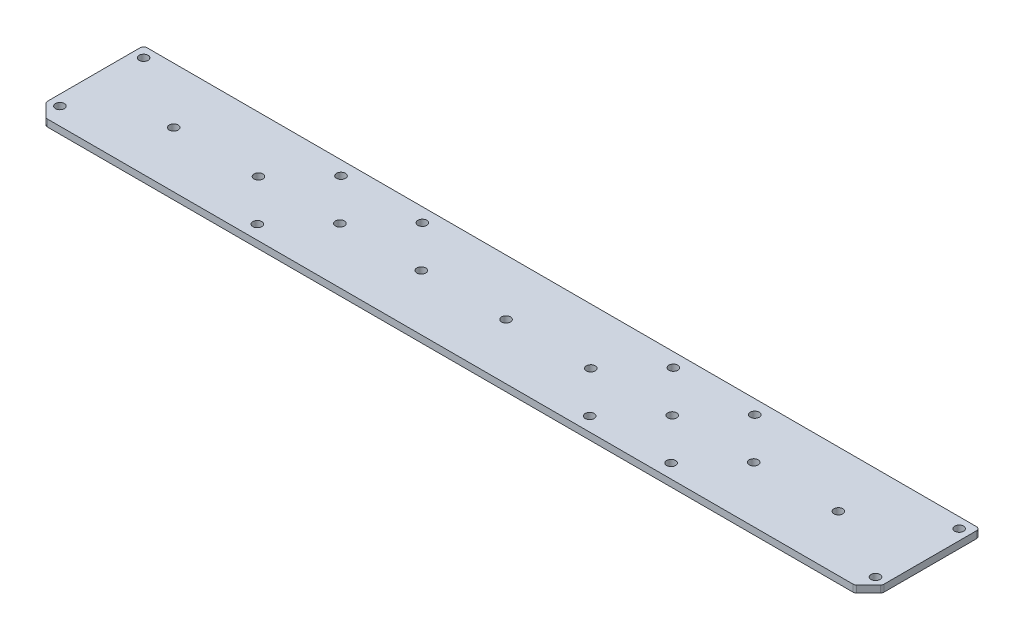
SolidWorks part; units mm, degrees
ref_plane "Front Plane" through (0, 0, 0) normal (0, 0, 1) x (1, 0, 0)
ref_plane "Top Plane" through (0, 0, 0) normal (0, 1, 0) x (1, 0, 0)
ref_plane "Right Plane" through (0, 0, 0) normal (1, 0, 0) x (0, 0, -1)
sketch "Sketch2" plane through (0, 0, 0) normal (0, 1, 0) x (1, 0, 0)
  line L0 (0, 7.0076) -> (0, 50.8)
  line L1 (0, 50.8) -> (381, 50.8)
  line L2 (381, 50.8) -> (381, 7.0076)
  line L3 (373.9924, 0) -> (7.0076, 0)
  line L4 (5.885, 0.465) -> (0.465, 5.885) construction
  line L5 (5.885, 0.465) -> (0.465, 5.885)
  line L6 (375.115, 0.465) -> (380.535, 5.885) construction
  line L7 (375.115, 0.465) -> (380.535, 5.885)
  line L8 (336.5758, 50.8) -> (379.4125, 50.8) construction
  arc A0 (5.885, 0.465) -> (7.0076, 0) centre (7.0076, 1.5875) ccw construction
  arc A1 (0, 7.0076) -> (0.465, 5.885) centre (1.5875, 7.0076) ccw construction
  arc A2 (5.885, 0.465) -> (7.0076, 0) centre (7.0076, 1.5875) ccw
  arc A3 (0, 7.0076) -> (0.465, 5.885) centre (1.5875, 7.0076) ccw
  arc A4 (373.9924, 0) -> (375.115, 0.465) centre (373.9924, 1.5875) ccw construction
  arc A6 (373.9924, 0) -> (375.115, 0.465) centre (373.9924, 1.5875) ccw
  arc A8 (380.535, 5.885) -> (381, 7.0076) centre (379.4125, 7.0076) ccw construction
  arc A9 (380.535, 5.885) -> (381, 7.0076) centre (379.4125, 7.0076) ccw
extrude "Boss-Extrude1" add sketch "Sketch2" along normal blind 3.175
sketch "Sketch3" plane through (0, 0, 0) normal (0, 1, 0) x (1, 0, 0)
  circle A25 centre (4.7625, 7.9375) radius 2.032 construction
  circle A31 centre (4.7625, 46.0375) radius 2.032 construction
  circle A63 centre (376.2375, 7.9375) radius 2.032 construction
  circle A64 centre (376.2375, 46.0375) radius 2.032 construction
  circle A67 centre (4.7625, 7.9375) radius 2.032
  circle A68 centre (4.7625, 46.0375) radius 2.032
  circle A72 centre (376.2375, 7.9375) radius 2.032
  circle A73 centre (376.2375, 46.0375) radius 2.032
  circle A123 centre (341.884, 25.4) radius 2.032 construction
  circle A124 centre (247.65, 44.45) radius 2.032 construction
  circle A125 centre (284.734, 44.45) radius 2.032 construction
  circle A128 centre (247.65, 6.35) radius 2.032 construction
  circle A129 centre (284.734, 6.35) radius 2.032 construction
  circle A132 centre (190.5, 25.4) radius 2.032 construction
  circle A135 centre (133.35, 44.45) radius 2.032 construction
  circle A136 centre (96.266, 44.45) radius 2.032 construction
  circle A137 centre (96.266, 6.35) radius 2.032 construction
  circle A140 centre (77.724, 25.4) radius 2.032 construction
  circle A141 centre (39.116, 25.4) radius 2.032 construction
  circle A142 centre (341.884, 25.4) radius 2.032
  circle A143 centre (247.65, 44.45) radius 2.032
  circle A144 centre (284.734, 44.45) radius 2.032
  circle A147 centre (247.65, 6.35) radius 2.032
  circle A148 centre (284.734, 6.35) radius 2.032
  circle A151 centre (190.5, 25.4) radius 2.032
  circle A154 centre (133.35, 44.45) radius 2.032
  circle A155 centre (96.266, 44.45) radius 2.032
  circle A156 centre (96.266, 6.35) radius 2.032
  circle A159 centre (77.724, 25.4) radius 2.032
  circle A160 centre (39.116, 25.4) radius 2.032
  circle A161 centre (151.892, 25.4) radius 2.032
  circle A162 centre (229.108, 25.4) radius 2.032
  circle A163 centre (266.192, 25.4) radius 2.032
  circle A164 centre (303.276, 25.4) radius 2.032
  circle A165 centre (151.892, 25.4) radius 2.3813 construction
  circle A166 centre (229.108, 25.4) radius 2.3813 construction
  circle A167 centre (266.192, 25.4) radius 2.3813 construction
  circle A168 centre (303.276, 25.4) radius 2.3813 construction
  circle A170 centre (114.808, 25.4) radius 2.032 construction
  circle A171 centre (114.808, 25.4) radius 2.032
extrude "Cut-Extrude1" cut sketch "Sketch3" along normal through all
fillet "Fillet1" radius 1.5875 2 edges at (0, 1.5875, -50.8) (381, 1.5875, -50.8)
